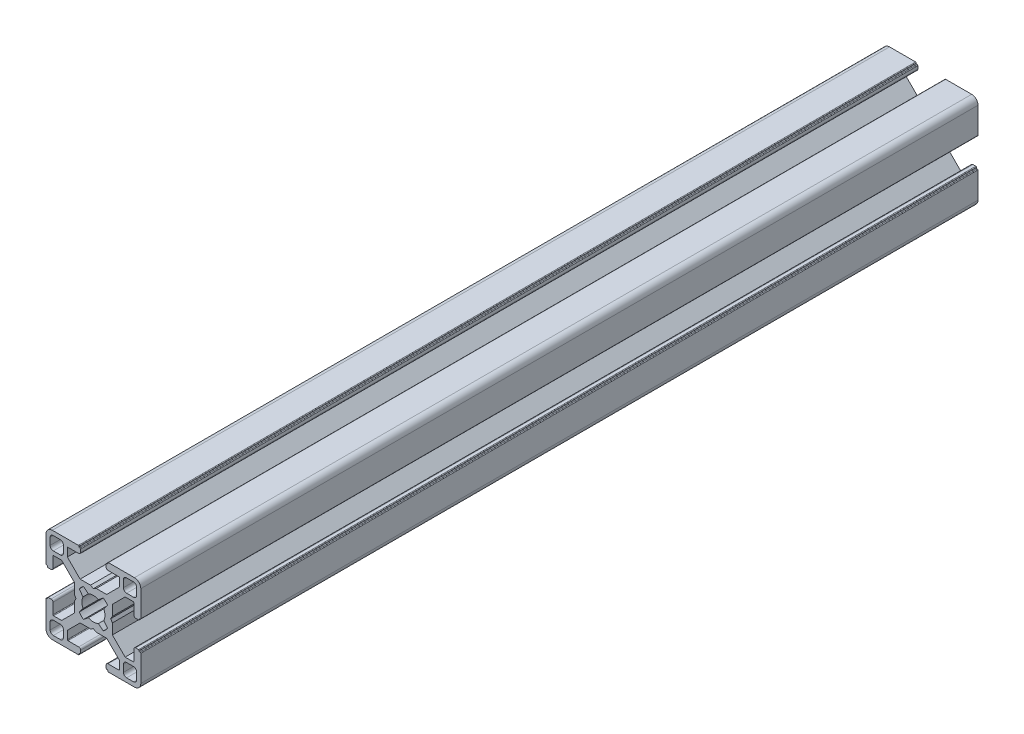
SolidWorks part; units mm, degrees
material "6061 Alloy"
ref_plane "Front" through (0, 0, 0) normal (0, 0, 1) x (1, 0, 0)
ref_plane "Top" through (0, 0, 0) normal (0, 1, 0) x (1, 0, 0)
ref_plane "Right" through (0, 0, 0) normal (1, 0, 0) x (0, 0, -1)
sketch "Sketch1" plane through (0, 0, 0) normal (0, 0, 1) x (1, 0, 0)
  line L0 (13.7, 12.7) -> (13.7, 10.5)
  line L1 (10.5, 9.5) -> (12.7, 9.5)
  line L2 (9.5, 12.7) -> (9.5, 10.5)
  line L3 (10.5, 13.7) -> (12.7, 13.7)
  line L4 (3.1359, 4.5184) -> (1.6001, 3.2806)
  line L5 (3.2806, 1.6001) -> (4.5053, 3.1547)
  line L6 (6.0045, 0.9) -> (5.4849, 0)
  line L7 (6.0045, 4.2045) -> (6.0045, 0.9)
  line L8 (0, -5.4849) -> (0.9, -6)
  line L9 (0.9, -6) -> (4.2045, -6)
  line L10 (4.2045, -6) -> (8.25, -10.05)
  line L11 (8.25, -10.05) -> (8.25, -12.6)
  line L12 (4.65, -12.8) -> (8.05, -12.8)
  line L13 (4.05, -14.3) -> (4.05, -13.4)
  line L14 (4.25, -14.5) -> (4.35, -14.5)
  line L15 (4.55, -14.8) -> (4.55, -14.7)
  line L16 (4.75, -15) -> (13, -15)
  line L17 (15, -13) -> (15, -4.75)
  line L18 (14.7, -4.55) -> (14.8, -4.55)
  line L19 (14.5, -4.35) -> (14.5, -4.25)
  line L20 (13.4, -4.05) -> (14.3, -4.05)
  line L21 (12.8, -8.05) -> (12.8, -4.65)
  line L22 (12.6, -8.25) -> (10.05, -8.25)
  line L23 (10.05, -8.25) -> (6.0045, -4.2045)
  line L24 (6.0045, -4.2045) -> (6.0045, -0.9)
  line L25 (6.0045, -0.9) -> (5.4849, 0)
  line L26 (10.05, 8.25) -> (6.0045, 4.2045)
  line L27 (12.6, 8.25) -> (10.05, 8.25)
  line L28 (12.8, 8.05) -> (12.8, 4.65)
  line L29 (13.4, 4.05) -> (14.3, 4.05)
  line L30 (14.5, 4.35) -> (14.5, 4.25)
  line L31 (14.7, 4.55) -> (14.8, 4.55)
  line L32 (15, 13) -> (15, 4.75)
  line L33 (4.75, 15) -> (13, 15)
  line L34 (4.55, 14.8) -> (4.55, 14.7)
  line L35 (4.25, 14.5) -> (4.35, 14.5)
  line L36 (4.05, 14.3) -> (4.05, 13.4)
  line L37 (4.65, 12.8) -> (8.05, 12.8)
  line L38 (8.25, 10.05) -> (8.25, 12.6)
  line L39 (4.2045, 6) -> (8.25, 10.05)
  line L40 (0.9, 6) -> (4.2045, 6)
  line L41 (0, 5.4849) -> (0.9, 6)
  line L42 (-13.7, -12.7) -> (-13.7, -10.5)
  line L43 (-10.5, -9.5) -> (-12.7, -9.5)
  line L44 (-9.5, -12.7) -> (-9.5, -10.5)
  line L45 (-10.5, -13.7) -> (-12.7, -13.7)
  line L46 (-3.1359, -4.5184) -> (-1.6001, -3.2806)
  line L47 (-3.2806, -1.6001) -> (-4.5053, -3.1547)
  line L48 (0, 5.4849) -> (-0.9, 6)
  line L49 (-0.9, 6) -> (-4.2045, 6)
  line L50 (-4.2045, 6) -> (-8.25, 10.05)
  line L51 (-8.25, 10.05) -> (-8.25, 12.6)
  line L52 (-4.65, 12.8) -> (-8.05, 12.8)
  line L53 (-4.05, 14.3) -> (-4.05, 13.4)
  line L54 (-4.25, 14.5) -> (-4.35, 14.5)
  line L55 (-4.55, 14.8) -> (-4.55, 14.7)
  line L56 (-4.75, 15) -> (-13, 15)
  line L57 (-15, 13) -> (-15, 4.75)
  line L58 (-14.7, 4.55) -> (-14.8, 4.55)
  line L59 (-14.5, 4.35) -> (-14.5, 4.25)
  line L60 (-13.4, 4.05) -> (-14.3, 4.05)
  line L61 (-12.8, 8.05) -> (-12.8, 4.65)
  line L62 (-12.6, 8.25) -> (-10.05, 8.25)
  line L63 (-10.05, 8.25) -> (-6.0045, 4.2045)
  line L64 (-6.0045, -0.9) -> (-5.4849, 0)
  line L65 (-6.0045, -4.2045) -> (-6.0045, -0.9)
  line L66 (-10.05, -8.25) -> (-6.0045, -4.2045)
  line L67 (-12.6, -8.25) -> (-10.05, -8.25)
  line L68 (-12.8, -8.05) -> (-12.8, -4.65)
  line L69 (-13.4, -4.05) -> (-14.3, -4.05)
  line L70 (-14.5, -4.35) -> (-14.5, -4.25)
  line L71 (-14.7, -4.55) -> (-14.8, -4.55)
  line L72 (-15, -13) -> (-15, -4.75)
  line L73 (-4.75, -15) -> (-13, -15)
  line L74 (-4.55, -14.8) -> (-4.55, -14.7)
  line L75 (-4.25, -14.5) -> (-4.35, -14.5)
  line L76 (-4.05, -14.3) -> (-4.05, -13.4)
  line L77 (3.2806, -1.6001) -> (4.5053, -3.1547)
  line L78 (3.1359, -4.5184) -> (1.6001, -3.2806)
  line L79 (-4.65, -12.8) -> (-8.05, -12.8)
  line L80 (-8.25, -10.05) -> (-8.25, -12.6)
  line L81 (-4.2045, -6) -> (-8.25, -10.05)
  line L82 (-0.9, -6) -> (-4.2045, -6)
  line L83 (0, -5.4849) -> (-0.9, -6)
  line L84 (10.5, -13.7) -> (12.7, -13.7)
  line L85 (9.5, -12.7) -> (9.5, -10.5)
  line L86 (10.5, -9.5) -> (12.7, -9.5)
  line L87 (13.7, -12.7) -> (13.7, -10.5)
  line L88 (-6.0045, 4.2045) -> (-6.0045, 0.9)
  line L89 (-6.0045, 0.9) -> (-5.4849, 0)
  line L90 (-3.2806, 1.6001) -> (-4.5053, 3.1547)
  line L91 (-3.1359, 4.5184) -> (-1.6001, 3.2806)
  line L92 (-10.5, 13.7) -> (-12.7, 13.7)
  line L93 (-9.5, 12.7) -> (-9.5, 10.5)
  line L94 (-10.5, 9.5) -> (-12.7, 9.5)
  line L95 (-13.7, 12.7) -> (-13.7, 10.5)
  line L96 (-23.4857, 0) -> (20.9308, 0) construction
  line L97 (0, 17.9563) -> (0, -17.361) construction
  arc A0 (13.7, 12.7) -> (12.7, 13.7) centre (12.7, 12.7) ccw
  arc A1 (12.7, 9.5) -> (13.7, 10.5) centre (12.7, 10.5) ccw
  arc A2 (9.5, 10.5) -> (10.5, 9.5) centre (10.5, 10.5) ccw
  arc A3 (10.5, 13.7) -> (9.5, 12.7) centre (10.5, 12.7) ccw
  arc A4 (1.6001, 3.2806) -> (-1.6001, 3.2806) centre (0, 0) ccw
  arc A5 (8.25, -12.6) -> (8.05, -12.8) centre (8.05, -12.6) cw
  arc A6 (4.65, -12.8) -> (4.05, -13.4) centre (4.65, -13.4) ccw
  arc A7 (4.05, -14.3) -> (4.25, -14.5) centre (4.25, -14.3) ccw
  arc A8 (4.35, -14.5) -> (4.55, -14.7) centre (4.35, -14.7) cw
  arc A9 (4.55, -14.8) -> (4.75, -15) centre (4.75, -14.8) ccw
  arc A10 (13, -15) -> (15, -13) centre (13, -13) ccw
  arc A11 (15, -4.75) -> (14.8, -4.55) centre (14.8, -4.75) ccw
  arc A12 (14.7, -4.55) -> (14.5, -4.35) centre (14.7, -4.35) cw
  arc A13 (14.5, -4.25) -> (14.3, -4.05) centre (14.3, -4.25) ccw
  arc A14 (13.4, -4.05) -> (12.8, -4.65) centre (13.4, -4.65) ccw
  arc A15 (12.8, -8.05) -> (12.6, -8.25) centre (12.6, -8.05) cw
  arc A16 (4.5053, 3.1547) -> (3.1359, 4.5184) centre (0, 0) ccw
  arc A17 (12.8, 8.05) -> (12.6, 8.25) centre (12.6, 8.05) ccw
  arc A18 (13.4, 4.05) -> (12.8, 4.65) centre (13.4, 4.65) cw
  arc A19 (14.5, 4.25) -> (14.3, 4.05) centre (14.3, 4.25) cw
  arc A20 (14.7, 4.55) -> (14.5, 4.35) centre (14.7, 4.35) ccw
  arc A21 (15, 4.75) -> (14.8, 4.55) centre (14.8, 4.75) cw
  arc A22 (13, 15) -> (15, 13) centre (13, 13) cw
  arc A23 (4.55, 14.8) -> (4.75, 15) centre (4.75, 14.8) cw
  arc A24 (4.35, 14.5) -> (4.55, 14.7) centre (4.35, 14.7) ccw
  arc A25 (4.05, 14.3) -> (4.25, 14.5) centre (4.25, 14.3) cw
  arc A26 (4.65, 12.8) -> (4.05, 13.4) centre (4.65, 13.4) cw
  arc A27 (8.25, 12.6) -> (8.05, 12.8) centre (8.05, 12.6) ccw
  arc A28 (-13.7, -12.7) -> (-12.7, -13.7) centre (-12.7, -12.7) ccw
  arc A29 (-12.7, -9.5) -> (-13.7, -10.5) centre (-12.7, -10.5) ccw
  arc A30 (-9.5, -10.5) -> (-10.5, -9.5) centre (-10.5, -10.5) ccw
  arc A31 (-10.5, -13.7) -> (-9.5, -12.7) centre (-10.5, -12.7) ccw
  arc A32 (-4.5053, -3.1547) -> (-3.1359, -4.5184) centre (0, 0) ccw
  arc A33 (-3.2806, 1.6001) -> (-3.2806, -1.6001) centre (0, 0) ccw
  arc A34 (-8.25, 12.6) -> (-8.05, 12.8) centre (-8.05, 12.6) cw
  arc A35 (-4.65, 12.8) -> (-4.05, 13.4) centre (-4.65, 13.4) ccw
  arc A36 (-4.05, 14.3) -> (-4.25, 14.5) centre (-4.25, 14.3) ccw
  arc A37 (-4.35, 14.5) -> (-4.55, 14.7) centre (-4.35, 14.7) cw
  arc A38 (-4.55, 14.8) -> (-4.75, 15) centre (-4.75, 14.8) ccw
  arc A39 (-13, 15) -> (-15, 13) centre (-13, 13) ccw
  arc A40 (-15, 4.75) -> (-14.8, 4.55) centre (-14.8, 4.75) ccw
  arc A41 (-14.7, 4.55) -> (-14.5, 4.35) centre (-14.7, 4.35) cw
  arc A42 (-14.5, 4.25) -> (-14.3, 4.05) centre (-14.3, 4.25) ccw
  arc A43 (-13.4, 4.05) -> (-12.8, 4.65) centre (-13.4, 4.65) ccw
  arc A44 (-12.8, 8.05) -> (-12.6, 8.25) centre (-12.6, 8.05) cw
  arc A45 (-4.5053, 3.1547) -> (-3.1359, 4.5184) centre (0, 0) cw
  arc A46 (-12.8, -8.05) -> (-12.6, -8.25) centre (-12.6, -8.05) ccw
  arc A47 (-13.4, -4.05) -> (-12.8, -4.65) centre (-13.4, -4.65) cw
  arc A48 (-14.5, -4.25) -> (-14.3, -4.05) centre (-14.3, -4.25) cw
  arc A49 (3.2806, 1.6001) -> (3.2806, -1.6001) centre (0, 0) cw
  arc A50 (4.5053, -3.1547) -> (3.1359, -4.5184) centre (0, 0) cw
  arc A51 (1.6001, -3.2806) -> (-1.6001, -3.2806) centre (0, 0) cw
  arc A52 (-14.7, -4.55) -> (-14.5, -4.35) centre (-14.7, -4.35) ccw
  arc A53 (-15, -4.75) -> (-14.8, -4.55) centre (-14.8, -4.75) cw
  arc A54 (-13, -15) -> (-15, -13) centre (-13, -13) cw
  arc A55 (-4.55, -14.8) -> (-4.75, -15) centre (-4.75, -14.8) cw
  arc A56 (10.5, -13.7) -> (9.5, -12.7) centre (10.5, -12.7) cw
  arc A57 (9.5, -10.5) -> (10.5, -9.5) centre (10.5, -10.5) cw
  arc A58 (12.7, -9.5) -> (13.7, -10.5) centre (12.7, -10.5) cw
  arc A59 (13.7, -12.7) -> (12.7, -13.7) centre (12.7, -12.7) cw
  arc A60 (-4.35, -14.5) -> (-4.55, -14.7) centre (-4.35, -14.7) ccw
  arc A61 (-4.05, -14.3) -> (-4.25, -14.5) centre (-4.25, -14.3) cw
  arc A62 (-4.65, -12.8) -> (-4.05, -13.4) centre (-4.65, -13.4) cw
  arc A63 (-8.25, -12.6) -> (-8.05, -12.8) centre (-8.05, -12.6) ccw
  arc A64 (-10.5, 13.7) -> (-9.5, 12.7) centre (-10.5, 12.7) cw
  arc A65 (-9.5, 10.5) -> (-10.5, 9.5) centre (-10.5, 10.5) cw
  arc A66 (-12.7, 9.5) -> (-13.7, 10.5) centre (-12.7, 10.5) cw
  arc A67 (-13.7, 12.7) -> (-12.7, 13.7) centre (-12.7, 12.7) cw
  point P81 (15, 15)
  point P82 (0, 15)
  point P203 (0, -15)
  point P204 (15, -15)
  point P206 (0, 0)
  point P207 (15, 0)
  point P219 (-15, 0)
  point P220 (-15, -15)
  point P221 (-15, 15)
extrude "Base-Extrude" add sketch "Sketch1" against normal blind 265
sketch "草图2" plane through (15, 0, 0) normal (1, 0, 0) x (0, 0, -1)
  line L0 (0, 15) -> (30, -15)
  line L1 (265, -15) -> (0, -15) construction
  line L2 (0, 4.75) -> (0, 13) construction
  line L3 (0, 15) -> (0, -15)
  line L4 (0, -15) -> (30, -15)
  line L5 (-13.0087, 11.9543) -> (-11.263, 12.8943)
  dimension "D1" = 45
